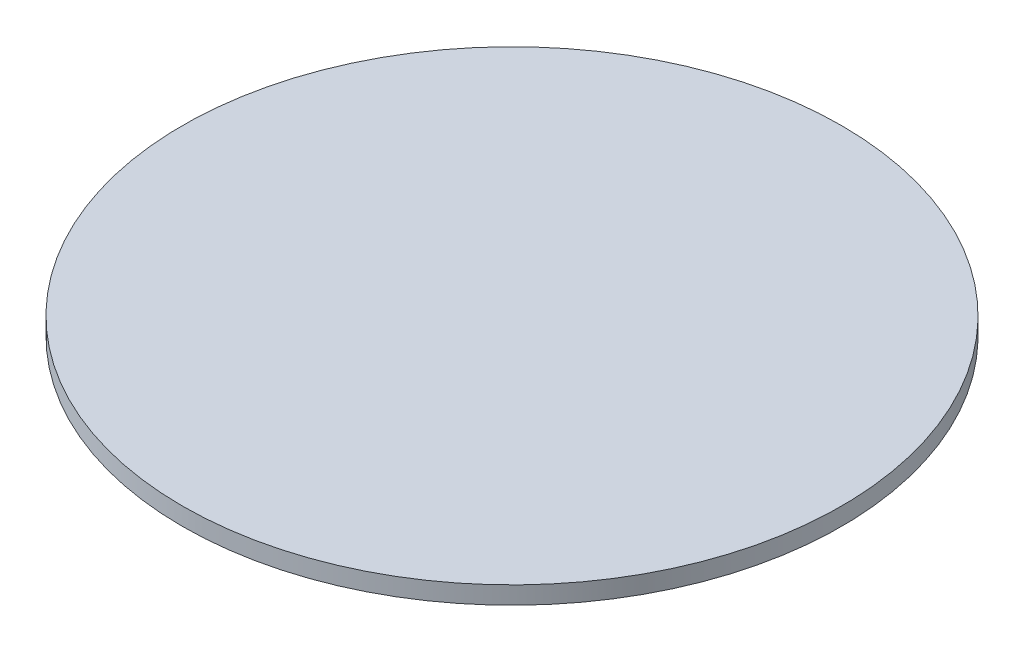
SolidWorks part; units mm, degrees
material "Silicon Dioxide"
ref_plane "Front Plane" through (0, 0, 0) normal (0, 0, 1) x (1, 0, 0)
ref_plane "Top Plane" through (0, 0, 0) normal (0, 1, 0) x (1, 0, 0)
ref_plane "Right Plane" through (0, 0, 0) normal (1, 0, 0) x (0, 0, -1)
sketch "Sketch1" plane through (0, 0, 0) normal (0, 1, 0) x (1, 0, 0)
  circle A0 centre (0, 0) radius 28
extrude "Boss-Extrude1" add sketch "Sketch1" along normal blind 1.5
scale "Scale1" scale about centroid uniform scaling yes scale factor 0.64
